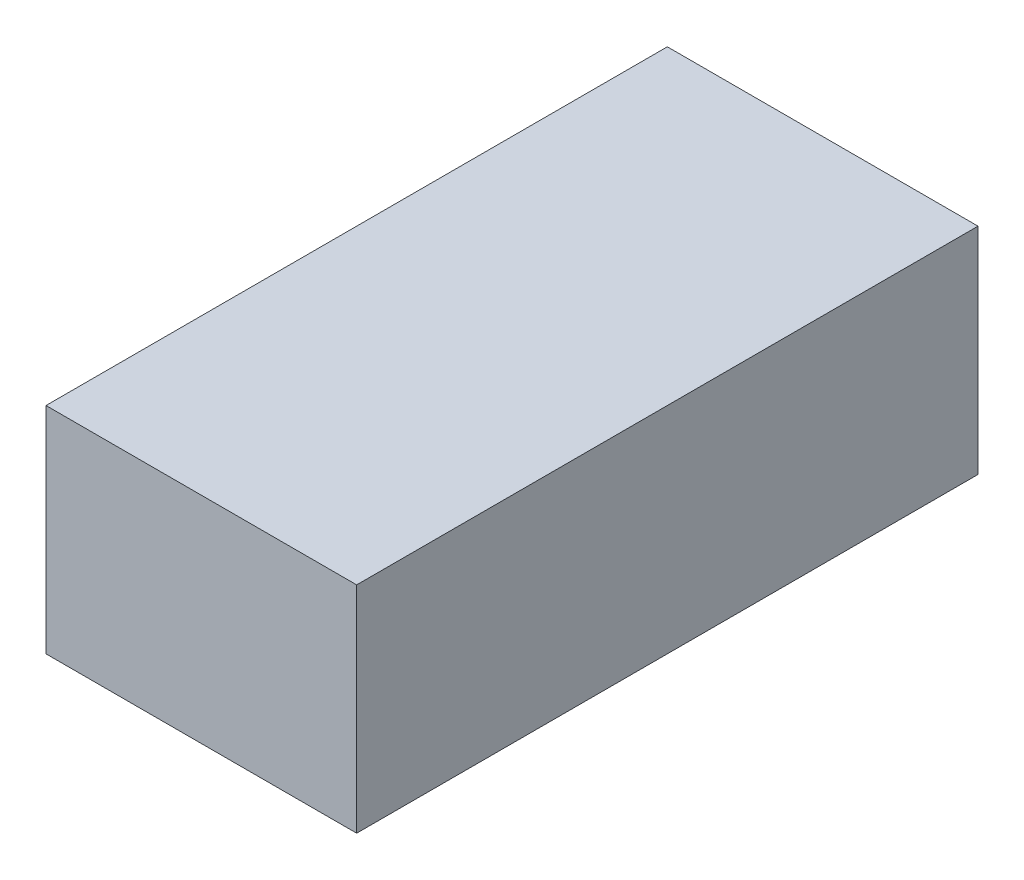
SolidWorks part; units mm, degrees
ref_plane "前视基准面" through (0, 0, 0) normal (0, 0, 1) x (1, 0, 0)
ref_plane "上视基准面" through (0, 0, 0) normal (0, 1, 0) x (1, 0, 0)
ref_plane "右视基准面" through (0, 0, 0) normal (1, 0, 0) x (0, 0, -1)
other "Configuration Table"
sketch "草图1" plane through (0, 0, 0) normal (0, 1, 0) x (1, 0, 0)
  line L5 (-6.5, -13) -> (6.5, -13)
  line L6 (-6.5, -13) -> (-6.5, 13)
  line L19 (-6.5, 13) -> (6.5, 13)
  line L20 (6.5, -13) -> (6.5, 13)
  line L29 (-6.5, -13) -> (6.5, 13) construction
  line L30 (-6.5, 13) -> (6.5, -13) construction
  point P0 (0, 0)
  dimension "D1" = 13
  dimension "D2" = 26
extrude "凸台-拉伸1" add sketch "草图1" along normal blind 9
